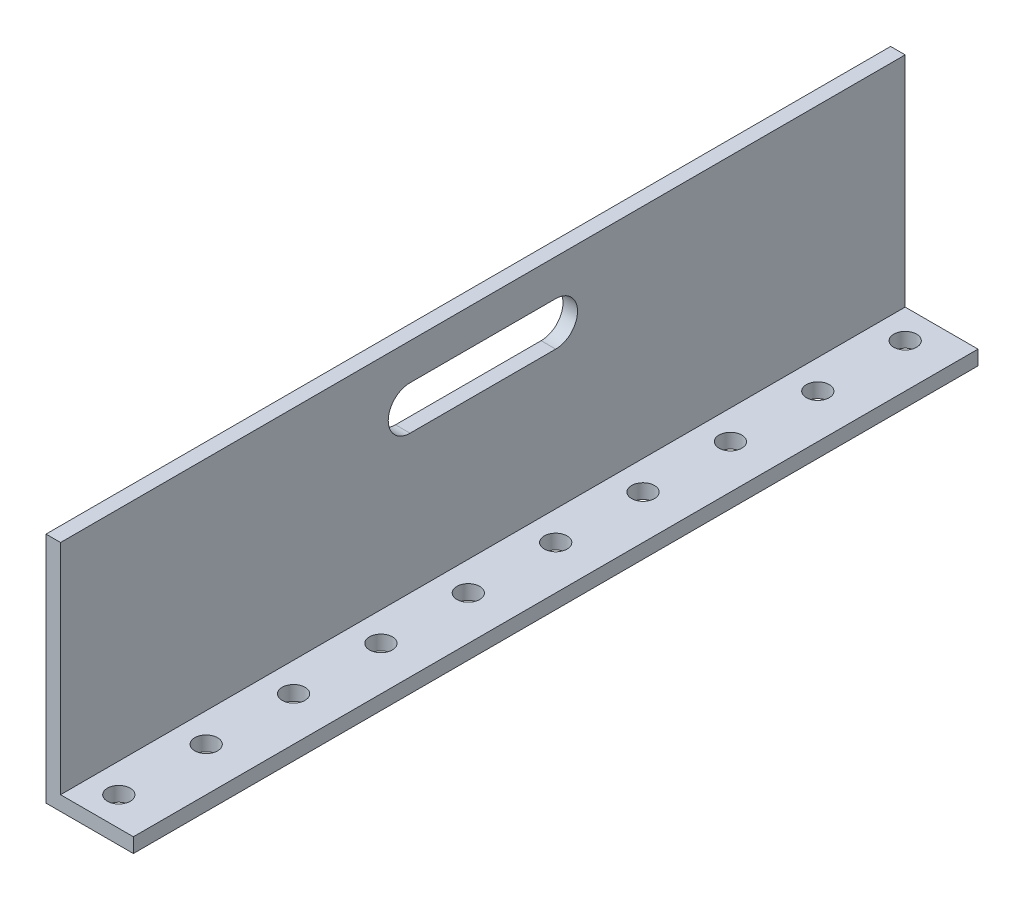
SolidWorks part; units mm, degrees
material "6061-T6 (SS)"
ref_plane "Front Plane" through (0, 0, 0) normal (0, 0, 1) x (1, 0, 0)
ref_plane "Top Plane" through (0, 0, 0) normal (0, 1, 0) x (1, 0, 0)
ref_plane "Right Plane" through (0, 0, 0) normal (1, 0, 0) x (0, 0, -1)
sketch "Sketch1" plane through (0, 0, 0) normal (0, 0, 1) x (1, 0, 0)
  line L1 (0, 0) -> (3.175, 0)
  line L2 (0, 0) -> (0, 50.8)
  line L3 (0, 50.8) -> (3.175, 50.8)
  line L4 (3.175, 0) -> (3.175, 50.8)
  line L5 (0, 0) -> (19.05, 0)
  line L6 (0, 0) -> (0, 3.175)
  line L7 (0, 3.175) -> (19.05, 3.175)
  line L8 (19.05, 0) -> (19.05, 3.175)
  dimension "D1" = 3.175
  dimension "D2" = 3.175
  dimension "D3" = 19.05
  dimension "D4" = 50.8
extrude "Boss-Extrude1" add sketch "Sketch1" along normal blind 184.15 contours L2 L7 L4 L3 | L7 L2 L1 L4 | L5 L8 L7 L4
sketch "Sketch2" plane through (0, 3.175, 0) normal (0, 1, 0) x (1, 0, 0)
  line L0 (3.175, 0) -> (19.05, 0) construction
  line L1 (3.175, -184.15) -> (3.175, 0) construction
  circle A0 centre (9.525, -6.35) radius 2.4892
  circle A1 centre (9.525, -25.4) radius 2.4892
  circle A2 centre (9.525, -44.45) radius 2.4892
  circle A3 centre (9.525, -63.5) radius 2.4892
  circle A4 centre (9.525, -82.55) radius 2.4892
  circle A5 centre (9.525, -101.6) radius 2.4892
  circle A6 centre (9.525, -120.65) radius 2.4892
  circle A7 centre (9.525, -139.7) radius 2.4892
  circle A8 centre (9.525, -158.75) radius 2.4892
  circle A9 centre (9.525, -177.8) radius 2.4892
  dimension "D1" = 4.9784
  dimension "D2" = 6.35
  dimension "D3" = 6.35
  dimension "D5" = 19.05
  dimension "D4" = 10
extrude "Cut-Extrude1" cut sketch "Sketch2" against normal blind 184.15
sketch "Sketch3" plane through (0, 0, 0) normal (-1, 0, 0) x (0, 0, 1)
  line L0 (76.2, 38.1) -> (107.95, 38.1) construction
  line L1 (76.2, 42.8625) -> (107.95, 42.8625)
  line L2 (76.2, 33.3375) -> (107.95, 33.3375)
  line L3 (184.15, 50.8) -> (0, 50.8) construction
  line L4 (184.15, 0) -> (0, 0) construction
  arc A0 (76.2, 42.8625) -> (76.2, 33.3375) centre (76.2, 38.1) ccw
  arc A1 (107.95, 33.3375) -> (107.95, 42.8625) centre (107.95, 38.1) ccw
  point P2 (92.075, 38.1)
  point P9 (92.075, 0)
  point P10 (0, 0)
  dimension "D2" = 4.7625
  dimension "D1" = 31.75
  dimension "D3" = 12.7
extrude "Cut-Extrude2" cut sketch "Sketch3" against normal blind 165.1
